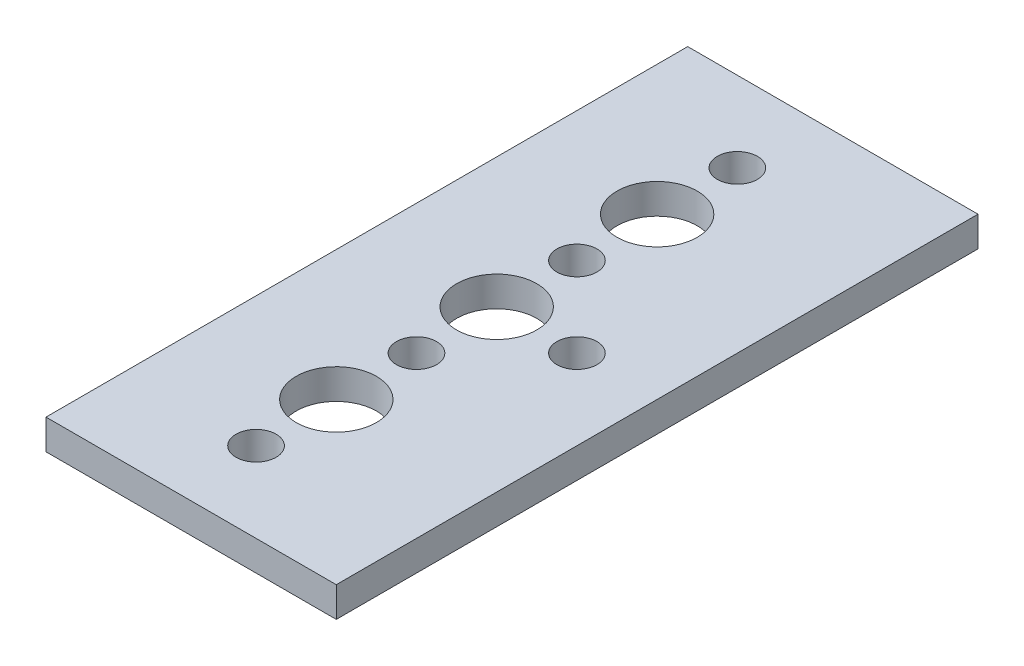
SolidWorks part; units mm, degrees
ref_plane "Front Plane" through (0, 0, 0) normal (0, 0, 1) x (1, 0, 0)
ref_plane "Top Plane" through (0, 0, 0) normal (0, 1, 0) x (1, 0, 0)
ref_plane "Right Plane" through (0, 0, 0) normal (1, 0, 0) x (0, 0, -1)
sketch "Sketch1" plane through (0, 0, 0) normal (0, 1, 0) x (1, 0, 0)
  line L0 (0, 0) -> (4, 0) construction
  line L2 (-12.95, 32) -> (16, 32)
  line L3 (-12.95, 32) -> (-12.95, -32)
  line L4 (-12.95, -32) -> (16, -32)
  line L5 (16, 32) -> (16, -32)
  circle A0 centre (0, 0) radius 4
  circle A1 centre (0, 8) radius 2
  circle A2 centre (8, 0) radius 2
  circle A3 centre (0, -8) radius 2
  circle A4 centre (-8, 0) radius 2 [skipped]
  circle A5 centre (0, 16) radius 4
  circle A6 centre (0, 24) radius 2
  circle A7 centre (0, -24) radius 2
  circle A8 centre (0, -16) radius 4
  point P14 (0, 0)
  point P25 (16, 0)
  dimension "D1" = 8
  dimension "D2" = 4
  dimension "D6" = 16
  dimension "D3" = 8
  dimension "D5" = 8
  dimension "D7" = 8
  dimension "D8" = 16
  dimension "D9" = 12.95
  dimension "D4" = 4
extrude "Boss-Extrude1" add sketch "Sketch1" along normal blind 3
sketch "Sketch2" plane through (-12.95, 0, 0) normal (-1, 0, 0) x (0, 0, 1)
  line L0 (32, 3) -> (-32, 3) construction
  line L1 (-15.278, 54.05) -> (34.633, 54.05) construction
  line L2 (-15.278, 54.05) -> (-15.278, 15.95) construction
  line L3 (-15.278, 15.95) -> (34.633, 15.95) construction
  line L4 (34.633, 54.05) -> (34.633, 15.95) construction
  line L5 (18, 54.05) -> (18, 3)
  line L6 (-18.278, 54.05) -> (18, 54.05)
  line L8 (-18.278, 54.05) -> (-18.278, 3)
  circle A0 centre (-8.548, 51) radius 1.6
  circle A1 centre (-8.548, 19) radius 1.6
  circle A2 centre (7.452, 19) radius 1.6
  circle A3 centre (7.452, 51) radius 1.6
  point P12 (0, 0)
  point P13 (0, 0)
  dimension "D3" = 3.2
  dimension "D1" = 38.1
  dimension "D2" = 49.911
  dimension "D4" = 3.05
  dimension "D5" = 3.05
  dimension "D6" = 16
  dimension "D7" = 6.73
  dimension "D8" = 15.278
  dimension "D9" = 12.95
  dimension "D10" = 18
  dimension "D11" = 3
